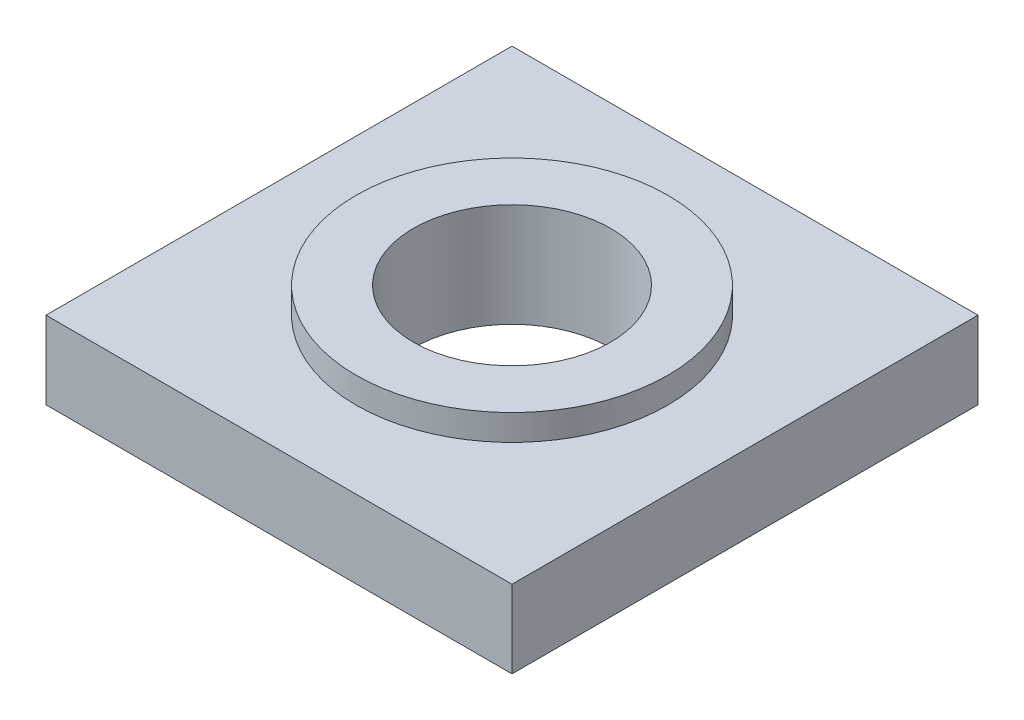
SolidWorks part; units mm, degrees
ref_plane "Front Plane" through (0, 0, 0) normal (0, 0, 1) x (1, 0, 0)
ref_plane "Top Plane" through (0, 0, 0) normal (0, 1, 0) x (1, 0, 0)
ref_plane "Right Plane" through (0, 0, 0) normal (1, 0, 0) x (0, 0, -1)
sketch "Sketch1" plane through (0, 0, 0) normal (0, 1, 0) x (1, 0, 0)
  line L1 (45, -45) -> (-45, -45)
  line L2 (45, -45) -> (45, 45)
  line L3 (45, 45) -> (-45, 45)
  line L4 (-45, -45) -> (-45, 45)
  line L5 (45, -45) -> (-45, 45) construction
  line L6 (45, 45) -> (-45, -45) construction
  circle A0 centre (0, 0) radius 19.05
  point P0 (0, 0)
  dimension "D1" = 90
extrude "Boss-Extrude1" add sketch "Sketch1" along normal blind 15
sketch "Sketch2" plane through (0, 15, 0) normal (0, 1, 0) x (1, 0, 0)
  circle A0 centre (0, 0) radius 30.1064
  circle A1 centre (0, 0) radius 19.05
extrude "Boss-Extrude3" add sketch "Sketch2" along normal blind 5
